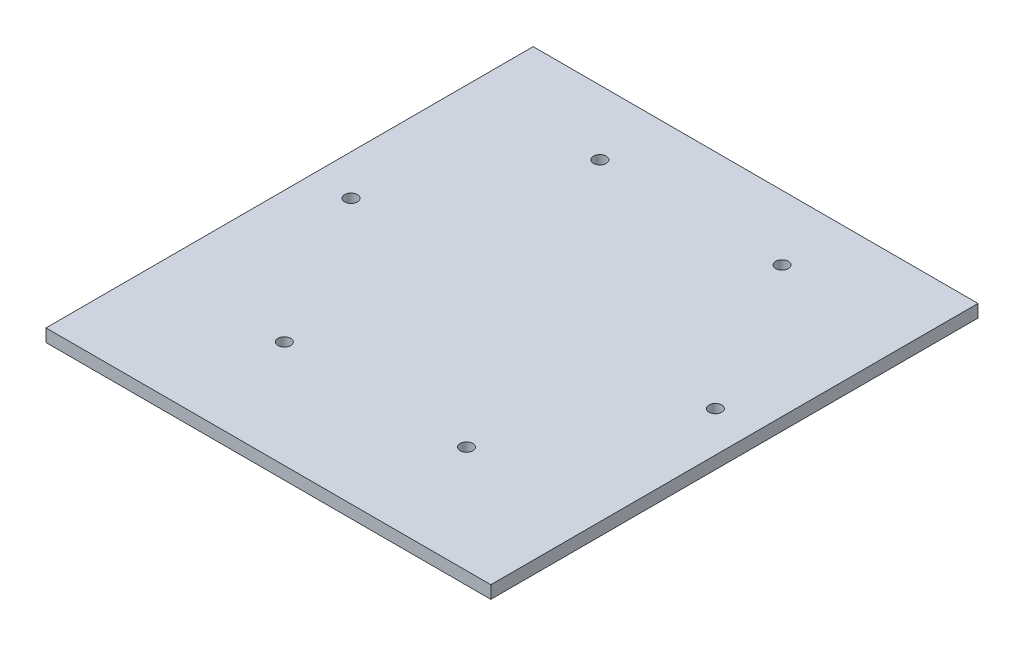
SolidWorks part; units mm, degrees
ref_plane "Front Plane" through (0, 0, 0) normal (0, 0, 1) x (1, 0, 0)
ref_plane "Top Plane" through (0, 0, 0) normal (0, 1, 0) x (1, 0, 0)
ref_plane "Right Plane" through (0, 0, 0) normal (1, 0, 0) x (0, 0, -1)
sketch "Sketch1" plane through (0, 0, 0) normal (0, 1, 0) x (1, 0, 0)
  line L1 (0, 0) -> (210, 0)
  line L2 (0, 0) -> (0, 230)
  line L3 (0, 230) -> (210, 230)
  line L4 (210, 0) -> (210, 230)
  circle A0 centre (105, 125) radius 100 construction
  circle A1 centre (62, 199.4782) radius 3
  circle A2 centre (148, 199.4782) radius 3
  circle A3 centre (191, 125) radius 3
  circle A4 centre (148, 50.5218) radius 3
  circle A5 centre (62, 50.5218) radius 3
  circle A6 centre (19, 125) radius 3
  point P21 (105, 125)
  dimension "D1" = 200
  dimension "D6" = 6
  dimension "D2" = 210
  dimension "D3" = 105
  dimension "D4" = 230
  dimension "D5" = 105
  dimension "D8" = 86
  dimension "D7" = 6
extrude "Boss-Extrude1" add sketch "Sketch1" along normal blind 6
sketch "Sketch3" plane through (0, 0, 0) normal (0, -1, 0) x (1, 0, 0)
  line L0 (210, 0) -> (210, -230) construction
  line L1 (0, 0) -> (210, 0)
  line L2 (0, 0) -> (0, -5)
  line L3 (0, -5) -> (210, -5)
  line L4 (210, 0) -> (210, -5)
  dimension "D1" = 5
